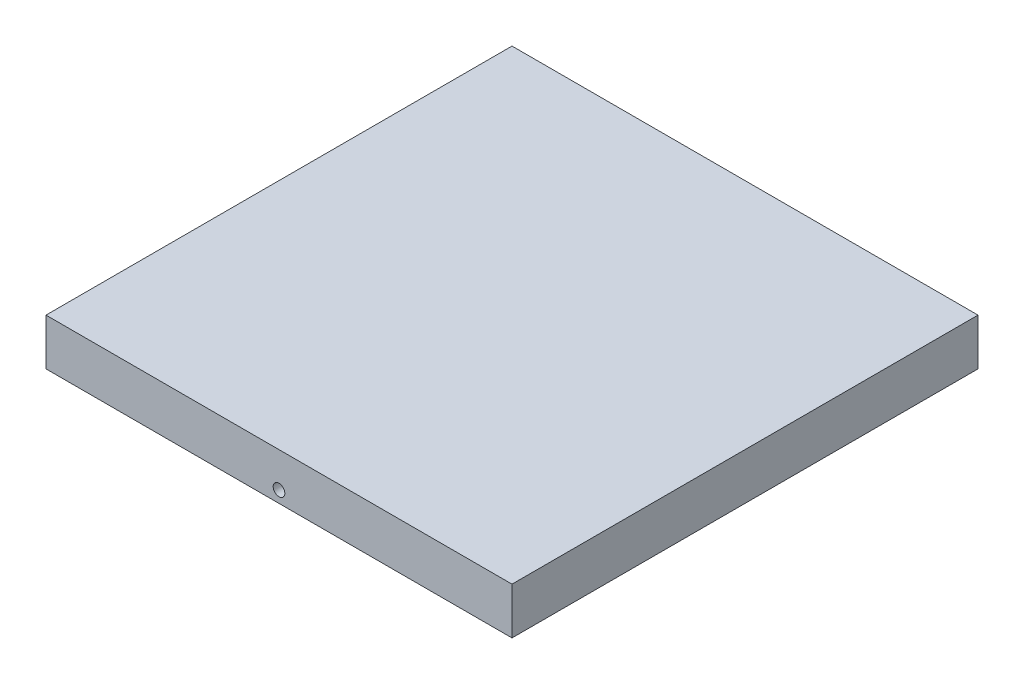
SolidWorks part; units mm, degrees
material "Mahogany"
ref_plane "Front Plane" through (0, 0, 0) normal (0, 0, 1) x (1, 0, 0)
ref_plane "Top Plane" through (0, 0, 0) normal (0, 1, 0) x (1, 0, 0)
ref_plane "Right Plane" through (0, 0, 0) normal (1, 0, 0) x (0, 0, -1)
sketch "Sketch1" plane through (0, 0, 0) normal (0, 1, 0) x (1, 0, 0)
  line L1 (-63.5, 63.5) -> (63.5, 63.5)
  line L2 (-63.5, 63.5) -> (-63.5, -63.5)
  line L3 (-63.5, -63.5) -> (63.5, -63.5)
  line L4 (63.5, 63.5) -> (63.5, -63.5)
  line L5 (-63.5, 63.5) -> (63.5, -63.5) construction
  line L6 (-63.5, -63.5) -> (63.5, 63.5) construction
  point P0 (0, 0)
  dimension "D1" = 127
  dimension "D2" = 127
extrude "Boss-Extrude1" add sketch "Sketch1" along normal blind 12.7
shell "Shell1" thickness 6.35
scale "Scale1" scale about origin uniform scaling yes scale factor 0.5
sketch "Sketch2" plane through (0, 0, 28.575) normal (0, 0, -1) x (-1, 0, 0)
  line L2 (-28.575, 3.175) -> (-28.575, 0) construction
  line L3 (28.575, 0) -> (-28.575, 0) construction
  circle A0 centre (0, 1.5875) radius 0.7938
  point P5 (0, 1.2039)
  point P8 (-28.575, 1.5875)
  point P9 (0, 0)
  dimension "D1" = 1.5875
extrude "Cut-Extrude2" cut sketch "Sketch2" against normal through all
